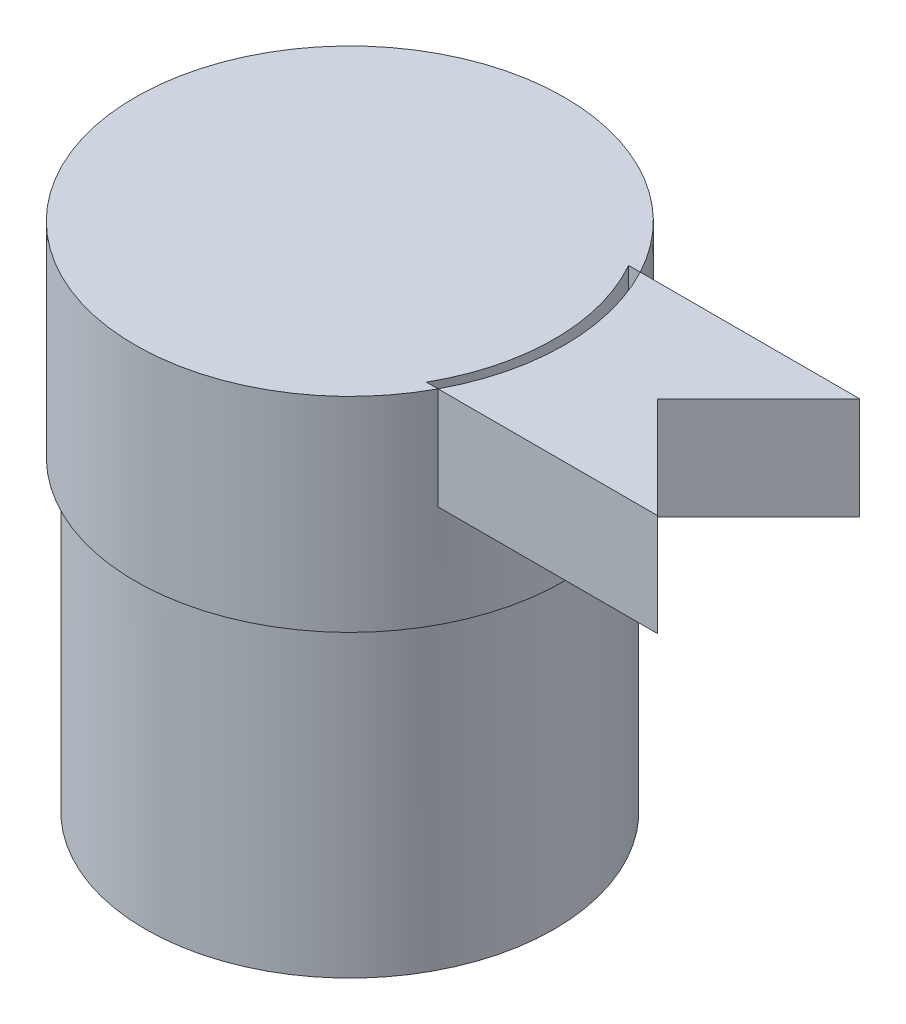
SolidWorks part; units mm, degrees
ref_plane "Front Plane" through (0, 0, 0) normal (0, 0, 1) x (1, 0, 0)
ref_plane "Top Plane" through (0, 0, 0) normal (0, 1, 0) x (1, 0, 0)
ref_plane "Right Plane" through (0, 0, 0) normal (1, 0, 0) x (0, 0, -1)
sketch "Sketch1" plane through (0, 0, 0) normal (0, 1, 0) x (1, 0, 0)
  circle A0 centre (0, 0) radius 100
extrude "Boss-Extrude1" add sketch "Sketch1" along normal blind 200
sketch "Sketch4" plane through (0, 200, 0) normal (0, 1, 0) x (1, 0, 0)
  line L0 (200, 49.4593) -> (150.5407, 0)
  line L1 (86.9124, -49.4593) -> (200, -49.4593)
  line L3 (86.9124, 49.4593) -> (200, 49.4593)
  line L5 (143.4562, 49.4593) -> (143.4562, -49.4593) construction
  line L6 (-10, 0) -> (150.5407, 0) construction
  line L7 (150.5407, 0) -> (200, -49.4593)
  circle A0 centre (0, 0) radius 100
  circle A1 centre (0, 0) radius 105
  point P4 (143.4562, 0)
  circle M9 centre (0, 0) radius 100
  dimension "D3" = 90
extrude "Boss-Extrude5" add sketch "Sketch4" along normal blind 50 contours A1 L1 L7 L0 L3 | M9 | L3 A1 L1 M9
sketch "Sketch5" plane through (0, 200, 0) normal (0, -1, 0) x (1, 0, 0)
  circle A0 centre (0, 0) radius 105
extrude "Boss-Extrude6" add sketch "Sketch5" along normal blind 50
